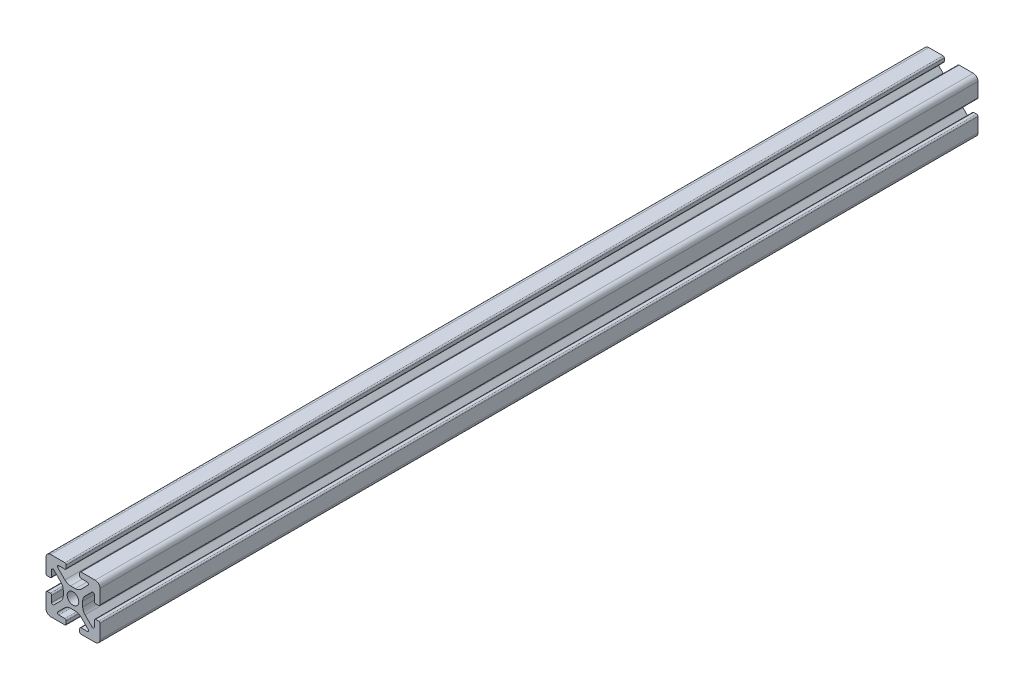
SolidWorks part; units mm, degrees
ref_plane "Front Plane" through (0, 0, 0) normal (0, 0, 1) x (1, 0, 0)
ref_plane "Top Plane" through (0, 0, 0) normal (0, 1, 0) x (1, 0, 0)
ref_plane "Right Plane" through (0, 0, 0) normal (1, 0, 0) x (0, 0, -1)
sketch "Sketch2" plane through (0, 0, 0) normal (0, 0, 1) x (1, 0, 0)
  line L0 (0, 10) -> (0, -10) construction
  line L1 (-10, 0) -> (10, 0) construction
  line L2 (2.5, -10) -> (10, -10)
  line L3 (10, -10) -> (10, -2.5)
  line L4 (2.5, -10) -> (2.5, -7.9246)
  line L5 (2.5, -7.9246) -> (6.4571, -7.9246)
  line L6 (6.4571, -7.9246) -> (2.1325, -3.6)
  line L7 (0, 0) -> (10, -10) construction
  line L8 (10, -2.5) -> (7.9246, -2.5)
  line L9 (7.9246, -2.5) -> (7.9246, -6.4571)
  line L10 (7.9246, -6.4571) -> (3.6, -2.1325)
  line L11 (5.7623, -4.2948) -> (4.2948, -5.7623) construction
  circle A0 centre (0, 0) radius 2.15
  arc A1 (5.25, -7.9246) -> (5.6036, -7.0711) centre (5.25, -7.4246) ccw construction
  point P8 (0, -3.6)
  point P16 (5.0286, -5.0286)
  dimension "Center Hole Diameter" = 4.3
  dimension "D3" = 0.5
  dimension "Rail Height" = 20
  dimension "Rail Width" = 20
  dimension "T-Slot Width" = 5
  dimension "Slot Depth" = 6.4
  dimension "Slot Inner Width" = 11.5
sketch "Sketch3" plane through (0, 0, 0) normal (1, 0, 0) x (0, 0, -1)
  line L0 (-304.8, -10) -> (304.8, -10) construction
  line L1 (-279.4, 0) -> (279.4, 0) construction
  line L2 (0, 10) -> (0, -10) construction
  line L3 (0, 10) -> (0, -10) construction
  point P6 (-279.4, 0)
  point P8 (279.4, 0)
  dimension "Length" = 609.6
  dimension "D1" = 25.4
sketch "Sketch4" plane through (0, 0, 0) normal (0, 0, 1) x (1, 0, 0)
  line L0 (3, -10) -> (8.25, -10)
  line L1 (2.5, -10) -> (10, -10) construction
  line L2 (2.5, -10) -> (2.5, -7.9246) construction
  line L3 (2.5, -7.9246) -> (6.4571, -7.9246) construction
  line L4 (2.5, -8.4246) -> (2.5, -9.5)
  line L5 (3, -7.9246) -> (5.25, -7.9246)
  line L6 (0, -3.6) -> (0.8898, -3.6)
  line L7 (6.4571, -7.9246) -> (2.1325, -3.6) construction
  line L8 (3.0112, -4.4787) -> (5.6036, -7.0711)
  line L9 (10, -10) -> (10, -2.5) construction
  line L10 (7.9246, -6.4571) -> (3.6, -2.1325) construction
  line L11 (7.9246, -2.5) -> (7.9246, -6.4571) construction
  line L12 (7.9246, -5.25) -> (7.9246, -3)
  line L13 (10, -2.5) -> (7.9246, -2.5) construction
  line L14 (8.4246, -2.5) -> (9.5, -2.5)
  line L15 (10, -3) -> (10, -8.25)
  line L16 (7.0711, -5.6036) -> (4.4787, -3.0112)
  line L17 (3.6, 0) -> (3.6, -0.8898)
  line L18 (-10, 0) -> (10, 0) construction
  line L19 (0, -3.6) -> (0, -2.15)
  line L20 (0, 10) -> (0, -10) construction
  line L21 (3.6, 0) -> (2.15, 0)
  arc A0 (2.5, -9.5) -> (3, -10) centre (3, -9.5) ccw
  arc A1 (5.25, -7.9246) -> (5.6036, -7.0711) centre (5.25, -7.4246) ccw construction
  arc A2 (2.5, -8.4246) -> (3, -7.9246) centre (3, -8.4246) cw
  arc A3 (5.25, -7.9246) -> (5.6036, -7.0711) centre (5.25, -7.4246) ccw
  arc A4 (0.8898, -3.6) -> (3.0112, -4.4787) centre (0.8898, -6.6) cw
  arc A5 (8.25, -10) -> (10, -8.25) centre (8.25, -8.25) ccw
  arc A6 (7.0711, -5.6036) -> (7.9246, -5.25) centre (7.4246, -5.25) ccw
  arc A7 (7.9246, -3) -> (8.4246, -2.5) centre (8.4246, -3) cw
  arc A8 (9.5, -2.5) -> (10, -3) centre (9.5, -3) cw
  arc A9 (4.4787, -3.0112) -> (3.6, -0.8898) centre (6.6, -0.8898) cw
  circle A10 centre (0, 0) radius 2.15 construction
  arc A11 (0, -2.15) -> (2.15, 0) centre (0, 0) ccw
  dimension "D1" = 1.75
  dimension "D2" = 3
extrude "Boss-Extrude1" add sketch "Sketch4" along normal mid plane 609.6
mirror "Mirror1" about plane through (0, 0, 0) normal (1, 0, 0) of bodies 134
mirror "Mirror2" about plane through (0, 0, 0) normal (0, 1, 0) of bodies 135
sketch "Sketch5" plane through (0, 0, -304.8) normal (0, 0, -1) x (-1, 0, 0)
  line L1 (-13.8311, 12.3183) -> (13.1641, 12.3183)
  line L2 (-13.8311, 12.3183) -> (-13.8311, -12.3688)
  line L3 (-13.8311, -12.3688) -> (13.1641, -12.3688)
  line L4 (13.1641, 12.3183) -> (13.1641, -12.3688)
extrude "Cut-Extrude1" cut sketch "Sketch5" against normal blind 284.025
equation "\"D3@Sketch2\"=\"T-Slot Width@Sketch2\"*0.1"
equation "\"D1@Sketch4\"=\"D3@Sketch2\"*3.5"
equation "\"D2@Sketch4\"=\"D3@Sketch2\"*6"
equation "\"D1@Boss-Extrude1\"=\"Length@Sketch3\""
